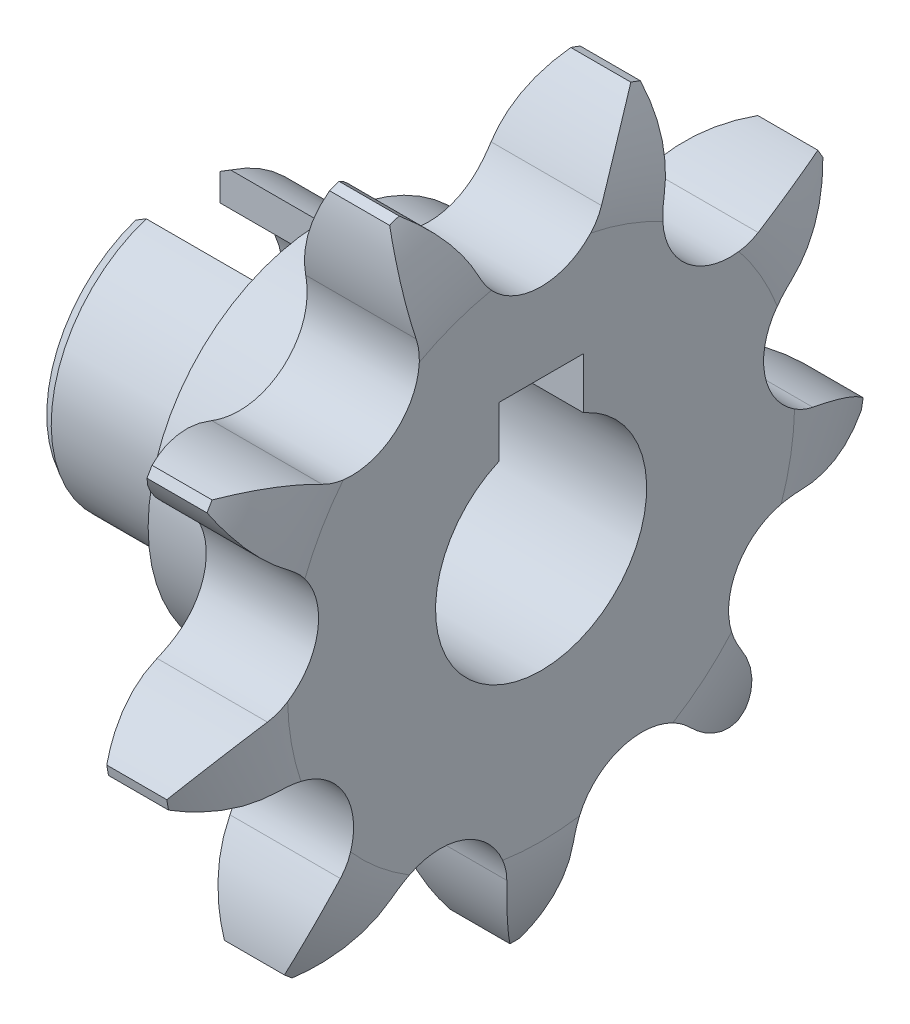
SolidWorks part; units mm, degrees
ref_plane "Plane1" through (0, 0, 0) normal (0, 0, 1) x (1, 0, 0)
ref_plane "Plane2" through (0, 0, 0) normal (0, 1, 0) x (1, 0, 0)
ref_plane "Plane3" through (0, 0, 0) normal (1, 0, 0) x (0, 0, -1)
sketch "Clipboard" plane through (0, 0, 0) normal (0, 1, 0) x (1, 0, 0)
  line L0 (0, 0) -> (9.4077, -1.49)
  line L1 (-15, 0) -> (100, 0) construction
  line L2 (0, 0) -> (-0.8203, 0.9272)
  line L3 (0, 0) -> (-8.8973, 3.4006)
  line L4 (0, 0) -> (3.0618, 0.4849)
  line L5 (0, 0) -> (-20.613, -7.688)
  line L6 (0, 0) -> (-4.4098, -2.9753)
  line L7 (-0.8203, 0.9272) -> (20.8459, 4.7475)
  line L8 (-76.2, 38.1) -> (-74.4, 38.1)
  line L9 (-73.3242, 40.7328) -> (-72.926, 40.7699)
  line L10 (-73.4529, 9.1872) -> (-63.2129, 9.1872)
  circle A0 centre (0, 0) radius 3.175
  circle A1 centre (0, 0) radius 8.4097
  circle A2 centre (0, 0) radius 9
  dimension "Dr" = 6.35
  dimension "MHD" = 16.8193
  dimension "Hub_dia" = 18
  dimension "Num_teeth" = 9
  dimension "Pitch" = 9.525
  dimension "Width" = 3.1
  dimension "Side_relief" = 1.238
  dimension "Side_radius" = 9.525
  dimension "Overall_len" = 22
  dimension "Show_teeth" = 9
  dimension "Thickness" = 5.3196
  dimension "OAL" = 22.0005
  dimension "T_dim" = 1.8
  dimension "Fillet_rad" = 0.4
  dimension "Face_width" = 5.32
  dimension "Num_strands" = 1
  dimension "Transv_pitch" = 10.24
  dimension "Plate_wid" = 8.26
sketch "BasProSke" plane through (0, 0, 0) normal (0, 1, 0) x (1, 0, 0)
  line L0 (-10, 0) -> (60, 0) construction
  line L1 (0, 0) -> (0, 12.0069)
  line L2 (0, 0) -> (5.3196, 0)
  line L3 (5.3196, 0) -> (5.3196, 12.0069)
  line L4 (4.0816, 16.7027) -> (1.238, 16.7027)
  arc A0 (0, 12.0069) -> (1.238, 16.7027) centre (9.525, 12.0069) cw
  arc A1 (5.3196, 12.0069) -> (4.0816, 16.7027) centre (-4.2054, 12.0069) ccw
  dimension "Thickness" = 5.3196
  dimension "D1" = 9.525
  dimension "G1" = 1.238
  dimension "G2" = 1.238
  dimension "Diameter" = 33.4055
revolve "Base-Revolve" add sketch "BasProSke" angle 360 about L0
sketch "TooCutSke" plane through (0, 0, 0) normal (1, 0, 0) x (0, 0, -1)
  line L0 (0, 13.9564) -> (2.9063, 12.6011) construction
  line L1 (0, 0) -> (0, 107) construction
  line L2 (0, 13.9564) -> (-10, 13.9564) construction
  line L3 (0, 13.9564) -> (-2.9063, 12.6011) construction
  arc A0 (2.9063, 12.6011) -> (5.9941, 16.1247) centre (10.503, 9.0588) cw
  arc A1 (2.9063, 12.6011) -> (-2.9063, 12.6011) centre (0, 13.9564) cw
  arc A2 (-2.9063, 12.6011) -> (-5.9941, 16.1247) centre (-10.503, 9.0588) ccw
  arc A3 (5.9941, 16.1247) -> (-5.9941, 16.1247) centre (0, 0) ccw
  dimension "R1" = 3.2067
  dimension "R2" = 8.382
  dimension "Overcut" = 17.2027
  dimension "Seat_radius" = 13.9564
  dimension "X" = 130
extrude "ToothCut" cut sketch "TooCutSke" along normal through all
pattern_circular "TeethCuts" count 9 every 40 about axis through (-10, 0, 0) along (1, 0, 0) of "ToothCut"
sketch "HubNeaOneSke" plane through (0, 0, 0) normal (-1, 0, 0) x (0, 0, 1)
  circle A0 centre (0, 0) radius 8.4097
  dimension "Diameter" = 16.8193
extrude "HubNearOne" add sketch "HubNeaOneSke" along normal blind 16.6809
fillet "HubNearOneFillet" radius 0.4 1 edges at (0, 0, -8.4097)
sketch "HubNeaBotSke" plane through (0, 0, 0) normal (-1, 0, 0) x (0, 0, 1)
  circle A0 centre (0, 0) radius 8.4097
  dimension "Diameter" = 16.8193
extrude "HubNearBoth" [suppressed] add sketch "HubNeaBotSke" along normal blind 8.3404
fillet "HubNearBothFillet" [suppressed] radius 0.4
ref_plane "FarPln" through (5.3196, 0, 0) normal (1, 0, 0) x (0, 0, -1)
sketch "HubFarSke" plane through (5.3196, 0, 0) normal (1, 0, 0) x (0, 0, -1)
  circle A0 centre (0, 0) radius 8.4097
  dimension "Diameter" = 16.8193
extrude "HubFar" [suppressed] add sketch "HubFarSke" along normal blind 8.3404
fillet "HubFarFillet" [suppressed] radius 0.4
sketch "BorSke" plane through (0, 0, 0) normal (1, 0, 0) x (0, 0, -1)
  circle A0 centre (0, 0) radius 5
  dimension "Diameter" = 10
extrude "Bore" cut sketch "BorSke" along normal mid plane 44.001
sketch "KeySke" plane through (0, 0, 0) normal (1, 0, 0) x (0, 0, -1)
  line L0 (-2, 0) -> (-2, 6.8)
  line L1 (-2, 6.8) -> (2, 6.8)
  line L2 (2, 6.8) -> (2, 0)
  line L3 (0, 0) -> (0, 34) construction
  line L4 (-2, 0) -> (2, 0)
  dimension "Offset" = 6.8
  dimension "Width" = 4
extrude "Keyway" [suppressed] cut sketch "KeySke" along normal mid plane 44.001
pattern_circular "Keyway2" [suppressed] count 2 every 90 about axis through (-10, 0, 0) along (1, 0, 0)
sketch "Sketch2" plane through (-16.6809, 0, 0) normal (-1, 0, 0) x (0, 0, 1)
  circle A0 centre (0, 0) radius 10
  dimension "D1" = 20
extrude "Cut-Extrude2" cut sketch "Sketch2" against normal blind 4.8
sketch "Sketch1" plane through (-11.8809, 0, 0) normal (-1, 0, 0) x (0, 0, 1)
  circle A0 centre (0, 0) radius 6.5
  dimension "D1" = 13
extrude "Cut-Extrude1" cut sketch "Sketch1" against normal blind 7 flip side to cut
chamfer "Chamfer1" distance 0.5 angle 30 1 edges at (-11.8809, 0, 6.5)
sketch "Sketch3" plane through (5.3196, 0, 0) normal (1, 0, 0) x (0, 0, -1)
  line L0 (-2, 3) -> (-2, 7)
  line L1 (-2, 3) -> (2, 3)
  line L2 (-2, 7) -> (2, 7)
  line L3 (2, 3) -> (2, 7)
  line L4 (-2, 3) -> (2, 7) construction
  line L5 (-2, 7) -> (2, 3) construction
  line L6 (0, 0) -> (0, 5) construction
  circle A0 centre (0, 0) radius 5 construction
  point P1 (0, 5)
  dimension "D1" = 4
extrude "Cut-Extrude3" cut sketch "Sketch3" against normal through all
equation "' \"Pitch@Clipboard\" = 12.7"
equation "' \"Num_strands@Clipboard\" = 1"
equation "' \"Num_teeth@Clipboard\" = 9"
equation "' \"Hub_dia@Clipboard\" = 50"
equation "' \"Overall_len@Clipboard\" = 3"
equation "' \"Diameter@BorSke\" = 12"
equation "' \"T_dim@Clipboard\" = 1"
equation "' \"Width@KeySke\" = 2"
equation "' \"Dr@Clipboard\" = 8.51"
equation "' \"Face_width@Clipboard\" = 7.2"
equation "' \"Side_radius@Clipboard\" = 12.7"
equation "' \"Side_relief@Clipboard\" = 1.27"
equation "' \"Transv_pitch@Clipboard\" = 13.92"
equation "' \"Show_teeth@Clipboard\" = 9"
equation "' \"Fillet_rad@Clipboard\" = 0.6"
equation "' \"Plate_wid@Clipboard\" = 11.8"
equation "\"Num_teeth@Clipboard\" = int( \"Num_teeth@Clipboard\" )"
equation "\"Num_teeth@Clipboard\" = ((sgn( \"Num_teeth@Clipboard\" - 5.0)+1)*( \"Num_teeth@Clipboard\" - 5.0))/2 +5.0"
equation "\"Num_teeth@Clipboard\" = ((sgn( \"Num_teeth@Clipboard\" - 200.0)-1)*( \"Num_teeth@Clipboard\" - 200.0))/-2 +200.0"
equation "\"MHD@Clipboard\" = \"Pitch@Clipboard\" * (1.0 / tan(3.14159265 / \"Num_teeth@Clipboard\" )) - 1.04 * \"Plate_wid@Clipboard\" - 0.76"
equation "\"Thickness@Clipboard\"  = \"Face_width@Clipboard\" + (\"Num_strands@Clipboard\" - 1) * \"Transv_pitch@Clipboard\""
equation "\"OAL@Clipboard\" = \"Thickness@Clipboard\" + 2 * \"Fillet_rad@Clipboard\" + 1"
equation "\"MHD@Clipboard\" = ((sgn( \"MHD@Clipboard\" - \"Hub_dia@Clipboard\" )-1)*( \"MHD@Clipboard\" - \"Hub_dia@Clipboard\" ))/-2+ \"Hub_dia@Clipboard\""
equation "\"OAL@Clipboard\" = ((sgn( \"OAL@Clipboard\" - \"Overall_len@Clipboard\" )+1)*( \"OAL@Clipboard\" - \"Overall_len@Clipboard\" ))/2 + \"Overall_len@Clipboard\" + 0.0005"
equation "\"Num_teeth@TeethCuts\" = int( \"Show_teeth@Clipboard\" ) + 1"
equation "\"Num_teeth@TeethCuts\" = ((sgn( \"Num_teeth@TeethCuts\" - \"Num_teeth@Clipboard\" )-1)*( \"Num_teeth@TeethCuts\" - \"Num_teeth@Clipboard\" ))/-2+ \"Num_teeth@Clipboard\""
equation "\"Num_teeth@TeethCuts\" = ((sgn( \"Num_teeth@TeethCuts\" - 2.0)+1)*( \"Num_teeth@TeethCuts\" - 2.0))/2 +2.0"
equation "\"Angle@TeethCuts\" = 360.0 / \"Num_teeth@Clipboard\""
equation "\"Seat_radius@TooCutSke\" = ( \"Pitch@Clipboard\" / 2.0) / sin(3.14159265 / \"Num_teeth@Clipboard\" ) - \"Dr@Clipboard\" / 2.0 + \"Dr@Clipboard\" * 0.505"
equation "\"R1@TooCutSke\"  = \"Dr@Clipboard\" * 0.505"
equation "\"X@TooCutSke\" = 140.0 - (90.0 / \"Num_teeth@Clipboard\")"
equation "\"R2@TooCutSke\" = 0.12 * \"Dr@Clipboard\" * ( \"Num_teeth@Clipboard\" + 2.0)"
equation "\"Overcut@TooCutSke\" = 0.5 + 0.625 * \"Pitch@Clipboard\" - 0.5 * \"Dr@Clipboard\"  +  \"Pitch@Clipboard\" / 2.0 / sin(3.14159265 / \"Num_teeth@Clipboard\" )"
equation "\"Diameter@BasProSke\" = 2.0 * ( 0.625 * \"Pitch@Clipboard\" - 0.5 * \"Dr@Clipboard\"  +  \"Pitch@Clipboard\" / 2.0 / sin(3.14159265 / \"Num_teeth@Clipboard\" ))"
equation "\"Thickness@BasProSke\"  = \"Thickness@Clipboard\""
equation "\"G1@BasProSke\" =  \"Side_relief@Clipboard\""
equation "\"G2@BasProSke\" =  \"Side_relief@Clipboard\""
equation "\"D1@BasProSke\" =  \"Side_radius@Clipboard\""
equation "\"Diameter@HubNeaOneSke\" = \"MHD@Clipboard\""
equation "\"Length@HubNearOne\" = \"OAL@Clipboard\" - \"Thickness@BasProSke\""
equation "\"Diameter@HubNeaBotSke\" = \"MHD@Clipboard\""
equation "\"Length@HubNearBoth\" = ( \"OAL@Clipboard\" - \"Thickness@BasProSke\" ) / 2.0"
equation "\"D1@HubNearOneFillet\" = \"Fillet_rad@Clipboard\""
equation "\"D1@HubNearBothFillet\" = \"Fillet_rad@Clipboard\""
equation "\"Thickness@FarPln\" = \"Thickness@BasProSke\""
equation "\"Diameter@HubFarSke\" = \"MHD@Clipboard\""
equation "\"Length@HubFar\" = ( \"OAL@Clipboard\" - \"Thickness@BasProSke\" ) / 2.0"
equation "\"D1@HubFarFillet\" = \"Fillet_rad@Clipboard\""
equation "\"D1@Bore\" = \"OAL@Clipboard\" * 2.0"
equation "\"D1@Keyway\" = \"OAL@Clipboard\" * 2.0"
equation "\"Offset@KeySke\" = \"T_dim@Clipboard\" + \"Diameter@BorSke\" / 2.0"
